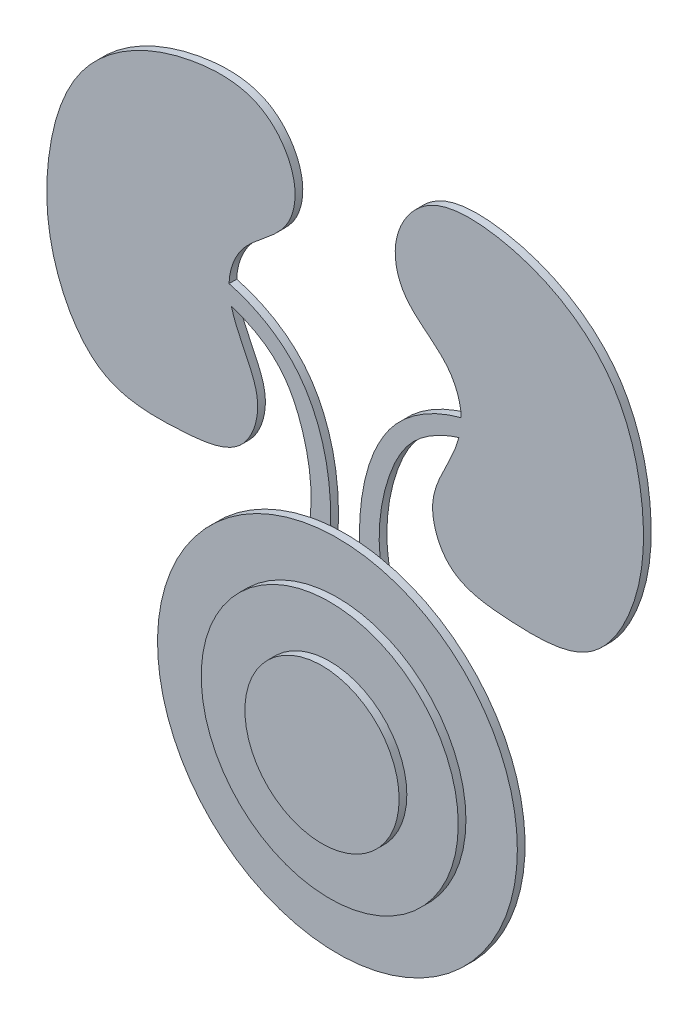
SolidWorks part; units mm, degrees
ref_plane "Front Plane" through (0, 0, 0) normal (0, 0, 1) x (1, 0, 0)
ref_plane "Top Plane" through (0, 0, 0) normal (0, 1, 0) x (1, 0, 0)
ref_plane "Right Plane" through (0, 0, 0) normal (1, 0, 0) x (0, 0, -1)
sketch "Sketch3" plane through (0, 0, 0) normal (0, 0, 1) x (1, 0, 0)
  line L0 (0, 94.186) -> (0, -105.814) construction
  line L1 (-28.8303, -28.6009) -> (-9.7264, -28.6009)
  line L2 (28.8303, -28.6009) -> (9.7264, -28.6009)
  spline S0 degree 3 poles (-45.1694, 63.2318) (-45.0392, 68.0404) (-41.3329, 78.4004) (-30.3375, 85.8067) (-21.0627, 95.0711) (-17.2403, 111.2298) (-30.5543, 132.3908) (-67.3102, 133.2461) (-105.166, 112.8816) (-117.5151, 70.2925) (-115.5283, 35.5567) (-96.7466, 3.6877) (-66.007, 3.7382) (-39.3819, 6.6159) (-31.4333, 28.8172) (-39.017, 43.0564) (-43.2556, 52.2634) (-44.2622, 56.0743) knots 0 0 0 0 0.039185 0.081822 0.105865 0.144209 0.207236 0.277955 0.419782 0.522441 0.617976 0.703159 0.786789 0.852005 0.901058 0.94824 0.980255 0.980255 0.980255 0.980255
  spline S1 degree 3 poles (-45.1694, 63.2318) (-35.5749, 60.7058) (-19.2033, 51.8848) (-8.5175, 30.2588) (-4.0644, 3.8528) (-6.6222, -15.5933) (-9.7264, -28.6009) knots 0 0 0 0 0.272897 0.476545 0.633441 1 1 1 1
  spline S2 degree 3 poles (-44.2622, 56.0743) (-37.4028, 53.9422) (-24.6345, 47.1682) (-16.1723, 28.9794) (-10.9167, 2.7733) (-16.0525, -18.642) (-28.8303, -28.6009) knots 0 0 0 0 0.214973 0.398291 0.567935 1 1 1 1
  spline S3 degree 3 poles (44.2622, 56.0743) (37.4028, 53.9422) (24.6345, 47.1682) (16.1723, 28.9794) (10.9167, 2.7733) (16.0525, -18.642) (28.8303, -28.6009) knots 0 0 0 0 0.214973 0.398291 0.567935 1 1 1 1
  spline S4 degree 3 poles (45.1694, 63.2318) (35.5749, 60.7058) (19.2033, 51.8848) (8.5175, 30.2588) (4.0644, 3.8528) (6.6222, -15.5933) (9.7264, -28.6009) knots 0 0 0 0 0.272897 0.476545 0.633441 1 1 1 1
  spline S5 degree 3 poles (45.1694, 63.2318) (45.0392, 68.0404) (41.3329, 78.4004) (30.3375, 85.8067) (21.0627, 95.0711) (17.2403, 111.2298) (30.5543, 132.3908) (67.3102, 133.2461) (105.166, 112.8816) (117.5151, 70.2925) (115.5283, 35.5567) (96.7466, 3.6877) (66.007, 3.7382) (39.3819, 6.6159) (31.4333, 28.8172) (39.017, 43.0564) (43.2556, 52.2634) (44.2622, 56.0743) knots 0 0 0 0 0.039185 0.081822 0.105865 0.144209 0.207236 0.277955 0.419782 0.522441 0.617976 0.703159 0.786789 0.852005 0.901058 0.94824 0.980255 0.980255 0.980255 0.980255
extrude "Boss-Extrude2" add sketch "Sketch3" against normal blind 3
sketch "Sketch4" plane through (0, 0, 0) normal (0, 0, 1) x (1, 0, 0)
  circle A0 centre (0, -68.3927) radius 70
  dimension "D1" = 140
extrude "Boss-Extrude3" add sketch "Sketch4" along normal blind 3
sketch "Sketch5" plane through (0, 0, 3) normal (0, 0, 1) x (1, 0, 0)
  circle A0 centre (0, -68.3927) radius 50
  dimension "D1" = 100
extrude "Boss-Extrude4" add sketch "Sketch5" along normal blind 3
sketch "Sketch6" plane through (0, 0, 6) normal (0, 0, 1) x (1, 0, 0)
  circle A0 centre (0, -68.3927) radius 30
  dimension "D1" = 60
extrude "Boss-Extrude5" add sketch "Sketch6" along normal blind 3
